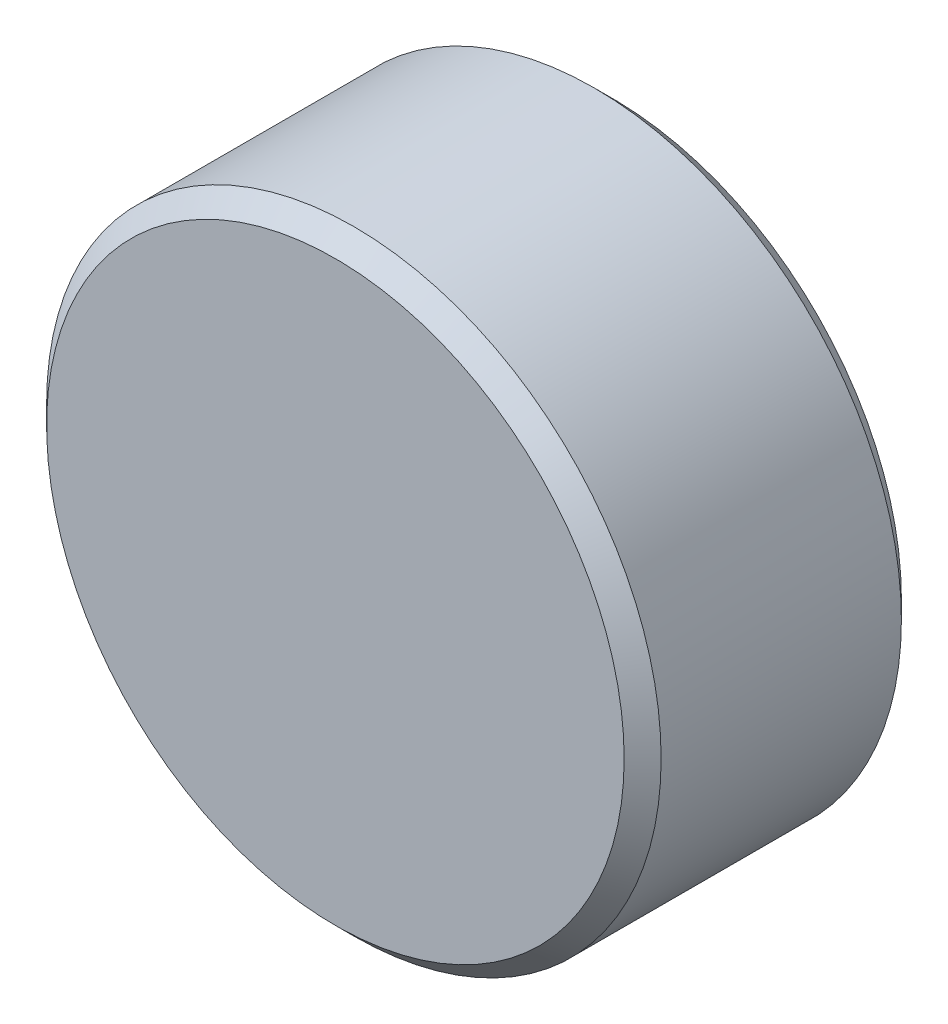
SolidWorks part; units mm, degrees
ref_plane "Plan de face" through (0, 0, 0) normal (0, 0, 1) x (1, 0, 0)
ref_plane "Plan de dessus" through (0, 0, 0) normal (0, 1, 0) x (1, 0, 0)
ref_plane "Plan de droite" through (0, 0, 0) normal (1, 0, 0) x (0, 0, -1)
sketch "Esquisse1" plane through (0, 0, 0) normal (0, 0, 1) x (1, 0, 0)
  circle A0 centre (0, 0) radius 33.25
extrude "Extrusion1" add sketch "Esquisse1" along normal blind 30
chamfer "Chanfrein1" distance 2 angle 45 1 edges at (33.25, 0, 30)
chamfer "Chanfrein2" distance 2 angle 45 1 edges at (33.25, 0, 0)
